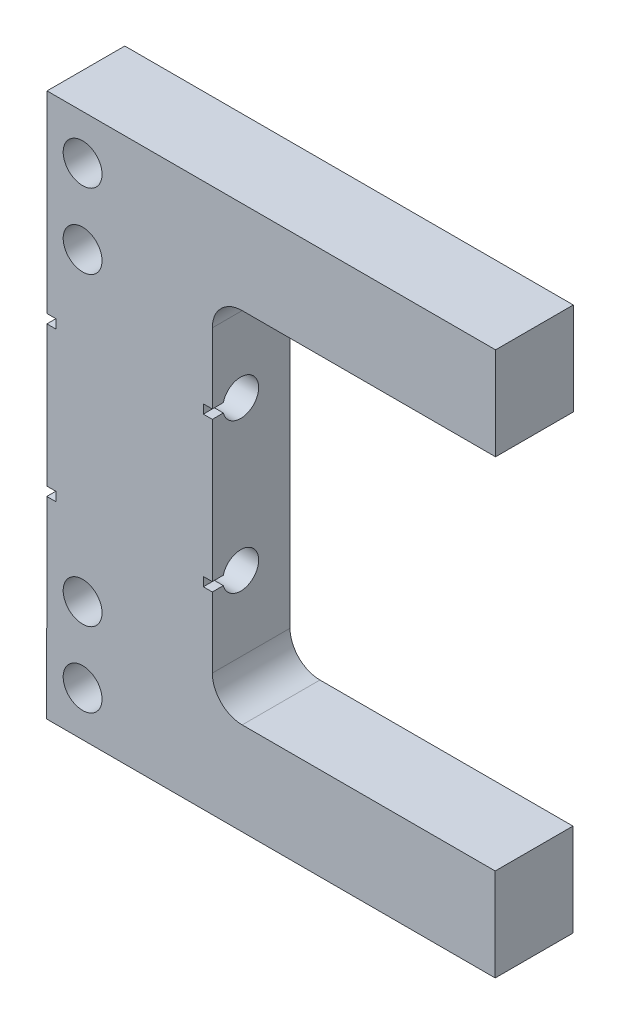
SolidWorks part; units mm, degrees
ref_plane "前基準面" through (0, 0, 0) normal (0, 0, 1) x (1, 0, 0)
ref_plane "上基準面" through (0, 0, 0) normal (0, 1, 0) x (1, 0, 0)
ref_plane "右基準面" through (0, 0, 0) normal (1, 0, 0) x (0, 0, -1)
sketch "草圖1" plane through (0, 0, 0) normal (0, 0, 1) x (1, 0, 0)
  line L0 (6.7985, 23.3296) -> (6.7985, 26.4296)
  line L1 (6.7985, 26.4296) -> (-2.6632, 26.4296)
  line L2 (-2.6632, 26.4296) -> (-2.6632, 38.4296)
  line L3 (-2.6632, 38.4296) -> (6.8103, 38.4296)
  line L4 (6.8103, 38.4296) -> (6.8103, 41.5296)
  line L5 (6.8103, 41.5296) -> (-8.1897, 41.5296)
  line L6 (-8.1897, 41.5296) -> (-8.2015, 23.3296)
  line L7 (-8.2015, 23.3296) -> (6.7985, 23.3296)
  dimension "D1" = 18.2
  dimension "D2" = 12
  dimension "D3" = 15
extrude "填料-伸長1" add sketch "草圖1" along normal blind 2.6
sketch "草圖2" plane through (0, 0, 2.6) normal (0, 0, 1) x (1, 0, 0)
  line L0 (-8.1897, 41.5296) -> (-8.2015, 23.3296) construction
  line L1 (-8.2006, 24.8296) -> (-7.0006, 24.8296) construction
  line L2 (-7.0006, 24.8296) -> (-7.0006, 23.3296) construction
  line L3 (-8.2015, 23.3296) -> (6.7985, 23.3296) construction
  line L4 (-7.0006, 24.8296) -> (-7.0006, 27.3296) construction
  line L5 (-7.0006, 41.5296) -> (-7.0006, 40.0296) construction
  line L6 (6.8103, 41.5296) -> (-8.1897, 41.5296) construction
  line L7 (-7.0006, 40.0296) -> (-7.0006, 37.5296) construction
  circle A0 centre (-7.0006, 24.8296) radius 0.65
  circle A1 centre (-7.0006, 27.3296) radius 0.65
  circle A2 centre (-7.0006, 40.0296) radius 0.65
  circle A3 centre (-7.0006, 37.5296) radius 0.65
  dimension "D1" = 1.3
  dimension "D2" = 1.2
  dimension "D3" = 2.5
  dimension "D4" = 1.5
extrude "除料-伸長1" cut sketch "草圖2" against normal through all
sketch "草圖3" plane through (-2.6632, 0, 0) normal (1, 0, 0) x (0, 0, -1)
  line L2 (-2.6, 41.5296) -> (0, 41.5296) construction
  line L3 (-2.6, 26.4296) -> (-2.6, 38.4296) construction
  circle A0 centre (-1.65, 34.9296) radius 0.6
  circle A1 centre (-1.65, 29.9296) radius 0.6
  dimension "D1" = 1.2
  dimension "D2" = 6.6
  dimension "D3" = 0.95
  dimension "D4" = 5
extrude "除料-伸長2" cut sketch "草圖3" against normal through all
sketch "草圖5" plane through (-8.2167, 0.0054, 0) normal (-1, 0.0007, 0) x (0, 0, 1)
  line L0 (2.6, 41.5243) -> (2.6, 23.3243) construction
  line L1 (2.2, 35.0743) -> (2.6, 35.0743)
  line L2 (2.2, 35.0743) -> (2.2, 34.7743)
  line L3 (2.2, 34.7743) -> (2.6, 34.7743)
  line L4 (2.6, 35.0743) -> (2.6, 34.7743)
  line L5 (2.6, 41.5243) -> (0, 41.5243) construction
  line L6 (2.2, 30.0743) -> (2.6, 30.0743)
  line L7 (2.2, 30.0743) -> (2.2, 29.7743)
  line L8 (2.2, 29.7743) -> (2.6, 29.7743)
  line L9 (2.6, 30.0743) -> (2.6, 29.7743)
  point P11 (2.2, 34.9243)
  point P12 (2.2, 29.9243)
  dimension "D1" = 0.4
  dimension "D2" = 0.3
  dimension "D3" = 5
  dimension "D4" = 6.6
extrude "除料-伸長3" cut sketch "草圖5" against normal blind 0.3
sketch "草圖7" plane through (-2.6632, 0, 0) normal (1, 0, 0) x (0, 0, -1)
  line L0 (-2.6, 26.4296) -> (-2.6, 38.4296) construction
  line L1 (-2.6, 29.7796) -> (-2.2, 29.7796)
  line L2 (-2.6, 29.7796) -> (-2.6, 30.0796)
  line L3 (-2.6, 30.0796) -> (-2.2, 30.0796)
  line L4 (-2.2, 29.7796) -> (-2.2, 30.0796)
  line L5 (-2.6, 41.5296) -> (0, 41.5296) construction
  line L6 (-2.6, 34.7796) -> (-2.2, 34.7796)
  line L7 (-2.6, 34.7796) -> (-2.6, 35.0796)
  line L8 (-2.6, 35.0796) -> (-2.2, 35.0796)
  line L9 (-2.2, 34.7796) -> (-2.2, 35.0796)
  point P10 (-2.2, 29.9296)
  point P11 (-2.2, 34.9296)
  dimension "D1" = 0.4
  dimension "D2" = 0.3
  dimension "D3" = 5
  dimension "D4" = 6.6
extrude "除料-伸長4" cut sketch "草圖7" against normal blind 0.3
fillet "圓角1" radius 1 2 edges at (-2.6632, 26.4296, 1.3) (-2.6632, 38.4296, 1.3)
